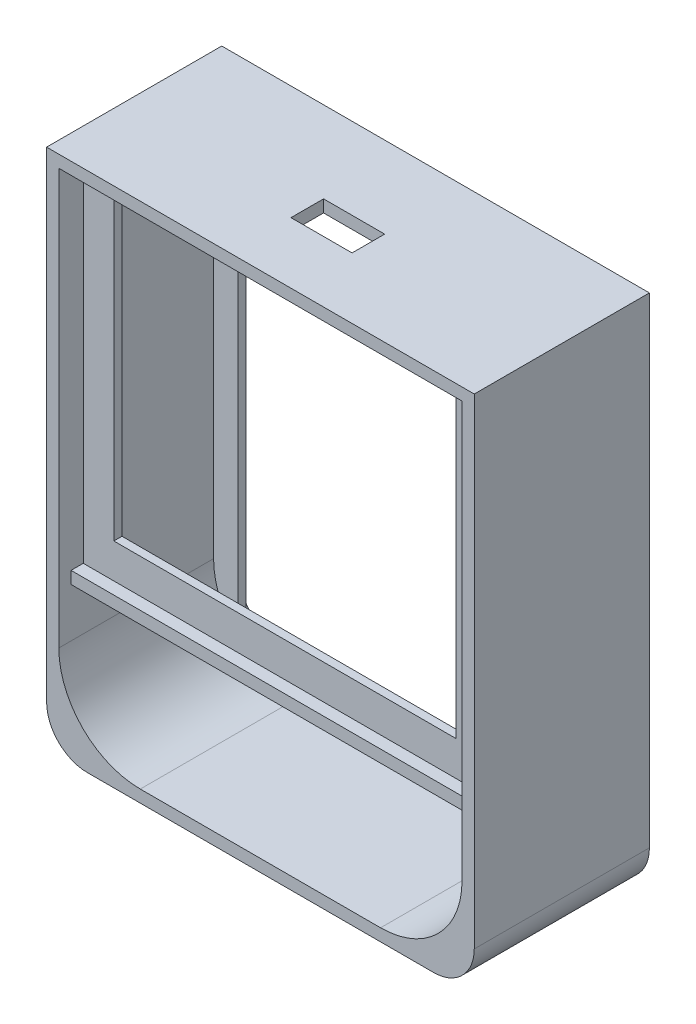
SolidWorks part; units mm, degrees
ref_plane "前视基准面" through (0, 0, 0) normal (0, 0, 1) x (1, 0, 0)
ref_plane "上视基准面" through (0, 0, 0) normal (0, 1, 0) x (1, 0, 0)
ref_plane "右视基准面" through (0, 0, 0) normal (1, 0, 0) x (0, 0, -1)
sketch "草图1" plane through (0, 0, 0) normal (0, 0, 1) x (1, 0, 0)
  line L1 (-52.5, 64) -> (52.5, 64)
  line L2 (-52.5, 64) -> (-52.5, -64)
  line L3 (-52.5, -64) -> (52.5, -64)
  line L4 (52.5, 64) -> (52.5, -64)
  line L5 (-52.5, 64) -> (52.5, -64) construction
  line L6 (-52.5, -64) -> (52.5, 64) construction
  point P0 (0, 0)
  dimension "D1" = 105
  dimension "D2" = 128
extrude "凸台-拉伸1" add sketch "草图1" along normal blind 43
sketch "草图2" plane through (0, 0, 43) normal (0, 0, 1) x (1, 0, 0)
  line L0 (-49.5, 61) -> (-49.5, -61)
  line L1 (-49.5, -61) -> (49.5, -61)
  line L2 (49.5, -61) -> (49.5, 61)
  line L3 (49.5, 61) -> (-49.5, 61)
  line L4 (-52.5, 64) -> (-52.5, -64) construction
  line L5 (52.5, -64) -> (52.5, 64) construction
  line L6 (-52.5, -64) -> (52.5, -64) construction
  line L7 (52.5, 64) -> (-52.5, 64) construction
  dimension "D1" = 3
  dimension "D2" = 3
  dimension "D3" = 3
  dimension "D4" = 3
extrude "切除-拉伸1" cut sketch "草图2" against normal blind 50
sketch "草图3" plane through (0, 61, 0) normal (0, -1, 0) x (1, 0, 0)
  line L13 (-49.5, 37) -> (-49.5, 35)
  line L14 (-49.5, 35) -> (49.5, 35)
  line L15 (49.5, 35) -> (49.5, 37)
  line L16 (49.5, 37) -> (-49.5, 37)
  line L17 (-52.5, 43) -> (52.5, 43) construction
  line L18 (-52.5, 43) -> (-52.5, 0) construction
  line L19 (52.5, 43) -> (52.5, 0) construction
  point P7 (-49.5, 36)
  dimension "D1" = 2
  dimension "D2" = 6
  dimension "D3" = 3
  dimension "D4" = 3
extrude "凸台-拉伸2" add sketch "草图3" along normal blind 90
sketch "草图4" plane through (0, 0, 37) normal (0, 0, 1) x (1, 0, 0)
  line L0 (-42, 52.5) -> (-42, -17.5)
  line L1 (-42, -17.5) -> (42, -17.5)
  line L2 (42, -17.5) -> (42, 52.5)
  line L3 (42, 52.5) -> (-42, 52.5)
  line L4 (-49.5, 61) -> (-49.5, -61) construction
  line L5 (49.5, -29) -> (49.5, 61) construction
  line L6 (49.5, 61) -> (-49.5, 61) construction
  dimension "D1" = 7.5
  dimension "D2" = 7.5
  dimension "D3" = 8.5
  dimension "D4" = 70
extrude "切除-拉伸2" cut sketch "草图4" against normal up to next
sketch "草图5" plane through (0, 0, 37) normal (0, 0, 1) x (1, 0, 0)
  line L0 (-49.5, -26) -> (-49.5, -29)
  line L1 (-49.5, -29) -> (-49.5, 61) construction
  line L2 (-49.5, -29) -> (49.5, -29)
  line L3 (49.5, -29) -> (49.5, -26)
  line L4 (49.5, -29) -> (49.5, 61) construction
  line L5 (49.5, -26) -> (-49.5, -26)
  dimension "D1" = 3
extrude "凸台-拉伸3" add sketch "草图5" along normal blind 3
sketch "草图6" plane through (0, 64, 0) normal (0, 1, 0) x (1, 0, 0)
  line L0 (-7.5, -20) -> (-7.5, -28)
  line L1 (-7.5, -28) -> (7.5, -28)
  line L2 (7.5, -28) -> (7.5, -20)
  line L3 (7.5, -20) -> (-7.5, -20)
  line L4 (52.5, 0) -> (-52.5, 0) construction
  line L5 (-52.5, -43) -> (-52.5, 0) construction
  dimension "D1" = 15
  dimension "D2" = 8
  dimension "D3" = 20
  dimension "D4" = 45
extrude "切除-拉伸3" cut sketch "草图6" against normal blind 10
sketch "草图8" plane through (0, 0, 37) normal (0, 0, 1) x (1, 0, 0)
  line L0 (-42, 52.5) -> (-42, 61)
  line L1 (49.5, 61) -> (-49.5, 61) construction
  line L2 (-42, 61) -> (42, 61)
  line L3 (42, 61) -> (42, 52.5)
  line L4 (42, 52.5) -> (-42, 52.5)
extrude "切除-拉伸4" cut sketch "草图8" against normal blind 2
sketch "草图9" plane through (49.5, 0, 0) normal (-1, 0, 0) x (0, 0, 1)
  line L6 (3, 61) -> (3, -61)
  line L7 (3, -61) -> (5, -61)
  line L8 (5, -61) -> (5, 61)
  line L9 (5, 61) -> (3, 61)
  line L10 (0, 64) -> (0, -64) construction
  line L11 (43, -64) -> (0, -64) construction
  line L12 (43, 64) -> (0, 64) construction
  dimension "D1" = 3
  dimension "D2" = 2
  dimension "D3" = 3
  dimension "D4" = 3
extrude "凸台-拉伸4" add sketch "草图9" along normal up to next
sketch "草图10" plane through (0, 0, 3) normal (0, 0, -1) x (-1, 0, 0)
  line L0 (-43.5, 55) -> (-43.5, -55)
  line L1 (-43.5, -55) -> (43.5, -55)
  line L2 (43.5, -55) -> (43.5, 55)
  line L3 (43.5, 55) -> (-43.5, 55)
  line L4 (-49.5, -61) -> (-49.5, 61) construction
  line L5 (49.5, 61) -> (-49.5, 61) construction
  line L6 (49.5, 61) -> (49.5, -61) construction
  line L7 (49.5, -61) -> (-49.5, -61) construction
  dimension "D1" = 6
  dimension "D2" = 6
  dimension "D3" = 6
  dimension "D4" = 6
extrude "切除-拉伸5" cut sketch "草图10" against normal blind 8
fillet "圆角10" radius 10 1 edges at (-52.5, -64, 21.5)
fillet "圆角11" radius 20 1 edges at (-49.5, -61, 1.5)
fillet "圆角12" radius 20 1 edges at (49.5, -61, 1.5)
fillet "圆角13" radius 10 1 edges at (52.5, -64, 21.5)
fillet "圆角14" radius 20 2 edges at (-49.5, 61, 1.5) (49.5, 61, 1.5)
fillet "圆角15" radius 20 1 edges at (49.5, -61, 24)
fillet "圆角16" radius 20 1 edges at (-49.5, -61, 24)
